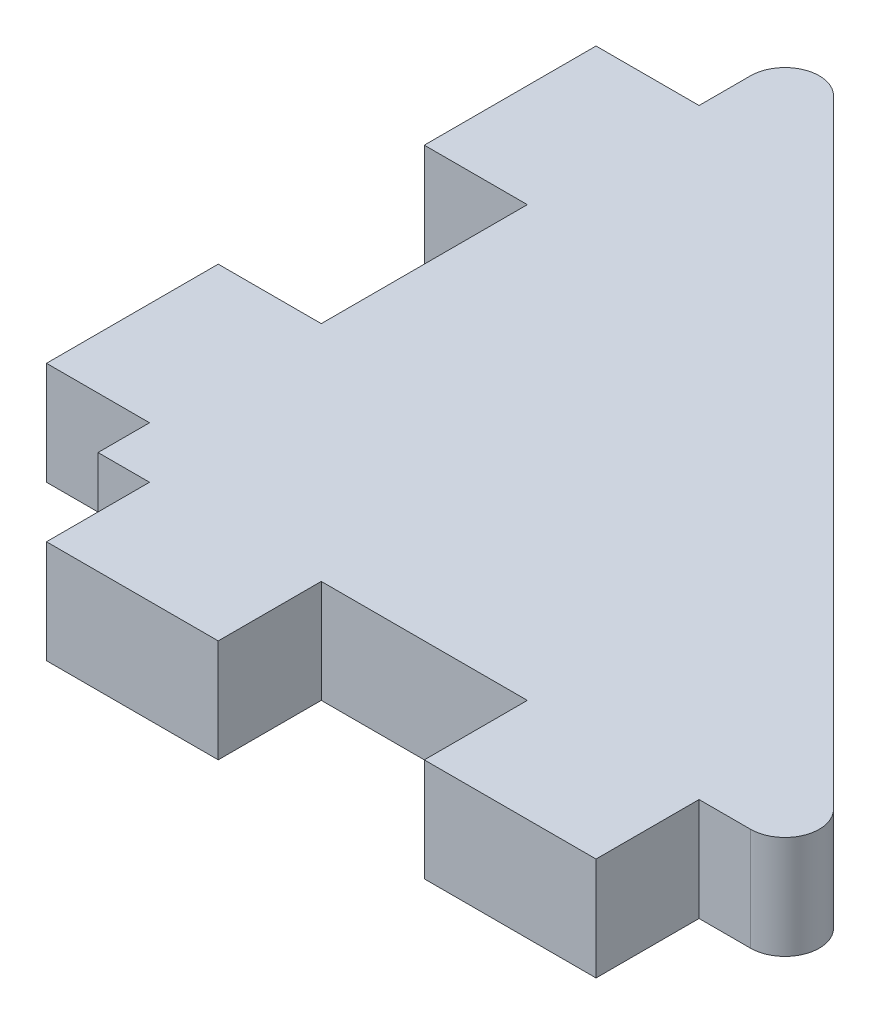
SolidWorks part; units mm, degrees
ref_plane "Front Plane" through (0, 0, 0) normal (0, 0, 1) x (1, 0, 0)
ref_plane "Top Plane" through (0, 0, 0) normal (0, 1, 0) x (1, 0, 0)
ref_plane "Right Plane" through (0, 0, 0) normal (1, 0, 0) x (0, 0, -1)
sketch "Sketch2" plane through (0, 0, 0) normal (0, 1, 0) x (1, 0, 0)
  line L0 (-38.9989, 19.1469) -> (-2.9989, -16.8531)
  line L2 (-42.4131, 17.7327) -> (-42.4131, 14.7327)
  line L3 (-42.4131, -20.2673) -> (-39.4131, -20.2673)
  line L5 (-29.4131, -20.2673) -> (-17.4131, -20.2673)
  line L6 (-42.4131, 14.7327) -> (-48.4131, 14.7327)
  line L8 (-42.4131, 4.7327) -> (-48.4131, 4.7327)
  line L9 (-48.4131, 14.7327) -> (-48.4131, 4.7327)
  line L10 (-42.4131, -7.2673) -> (-48.4131, -7.2673)
  line L12 (-42.4131, -17.2673) -> (-48.4131, -17.2673)
  line L13 (-48.4131, -7.2673) -> (-48.4131, -17.2673)
  line L15 (-39.4131, -20.2673) -> (-39.4131, -26.2673)
  line L16 (-39.4131, -26.2673) -> (-29.4131, -26.2673)
  line L17 (-29.4131, -20.2673) -> (-29.4131, -26.2673)
  line L19 (-17.4131, -20.2673) -> (-17.4131, -26.2673)
  line L20 (-17.4131, -26.2673) -> (-7.4131, -26.2673)
  line L21 (-7.4131, -20.2673) -> (-7.4131, -26.2673)
  line L22 (-7.4131, -20.2673) -> (-4.4131, -20.2673)
  line L23 (-42.4131, -17.2673) -> (-42.4131, -20.2673)
  line L24 (-42.4131, 4.7327) -> (-42.4131, -7.2673)
  arc A0 (-38.9989, 19.1469) -> (-42.4131, 17.7327) centre (-40.4131, 17.7327) ccw
  arc A1 (-4.4131, -20.2673) -> (-2.9989, -16.8531) centre (-4.4131, -18.2673) ccw
  dimension "D1" = 2
  dimension "D2" = 2
  dimension "D3" = 6
  dimension "D4" = 10
  dimension "D5" = 6
  dimension "D6" = 10
  dimension "D7" = 10
  dimension "D8" = 6
  dimension "D9" = 6
  dimension "D10" = 10
  dimension "D11" = 3
  dimension "D12" = 3
  dimension "D13" = 12
  dimension "D14" = 3
  dimension "D15" = 12
  dimension "D16" = 3
extrude "Boss-Extrude1" add sketch "Sketch2" along normal blind 6
